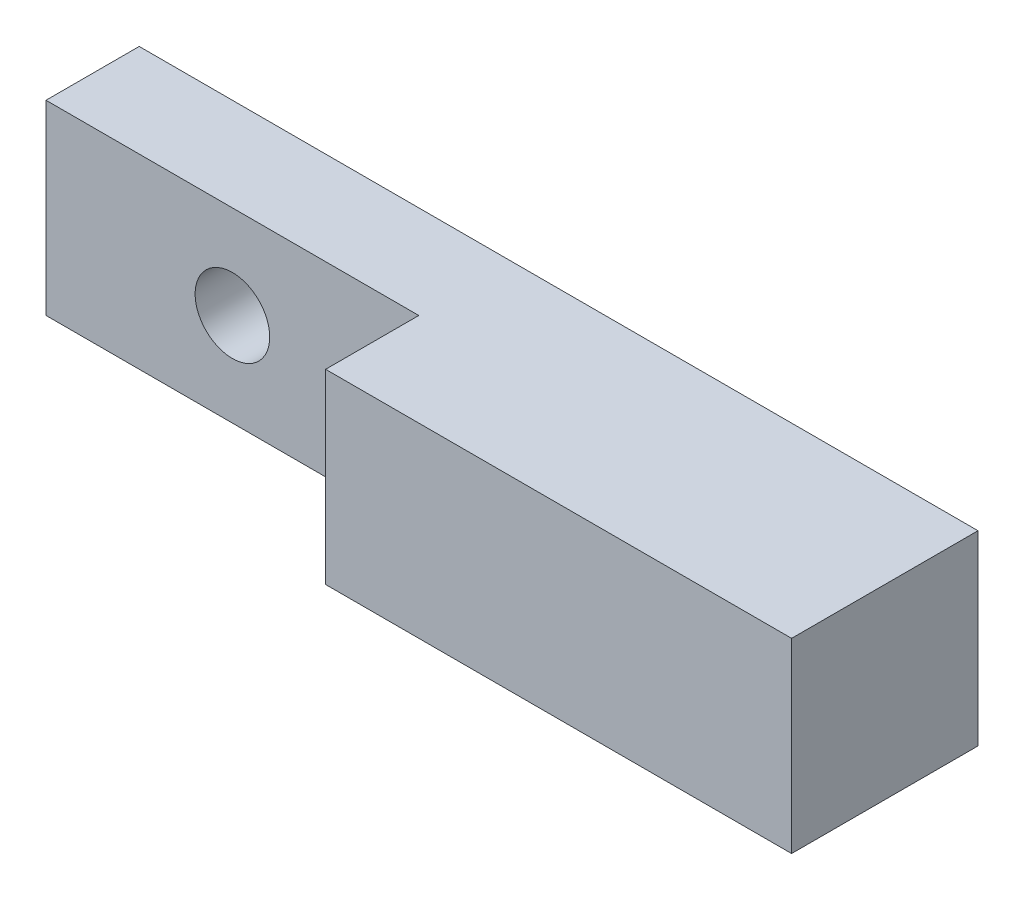
SolidWorks part; units mm, degrees
ref_plane "Front Plane" through (0, 0, 0) normal (0, 0, 1) x (1, 0, 0)
ref_plane "Top Plane" through (0, 0, 0) normal (0, 1, 0) x (1, 0, 0)
ref_plane "Right Plane" through (0, 0, 0) normal (1, 0, 0) x (0, 0, -1)
sketch "Sketch1" plane through (0, 0, 0) normal (0, 0, 1) x (1, 0, 0)
  line L1 (0, 0) -> (45, 0)
  line L2 (0, 0) -> (0, 10)
  line L3 (0, 10) -> (45, 10)
  line L4 (45, 0) -> (45, 10)
  dimension "D1" = 45
  dimension "D2" = 10
extrude "Boss-Extrude1" add sketch "Sketch1" along normal blind 10
sketch "Sketch2" plane through (0, 0, 10) normal (0, 0, 1) x (1, 0, 0)
  line L0 (0, 0) -> (45, 0) construction
  line L1 (0, 10) -> (20, 10)
  line L2 (0, 10) -> (0, 0)
  line L3 (0, 0) -> (20, 0)
  line L4 (20, 10) -> (20, 0)
  dimension "D1" = 20
extrude "Cut-Extrude1" cut sketch "Sketch2" against normal blind 5
sketch "Sketch3" plane through (0, 0, 5) normal (0, 0, 1) x (1, 0, 0)
  circle A0 centre (10, 5) radius 2
  dimension "D1" = 4
extrude "Cut-Extrude2" cut sketch "Sketch3" against normal blind 5
